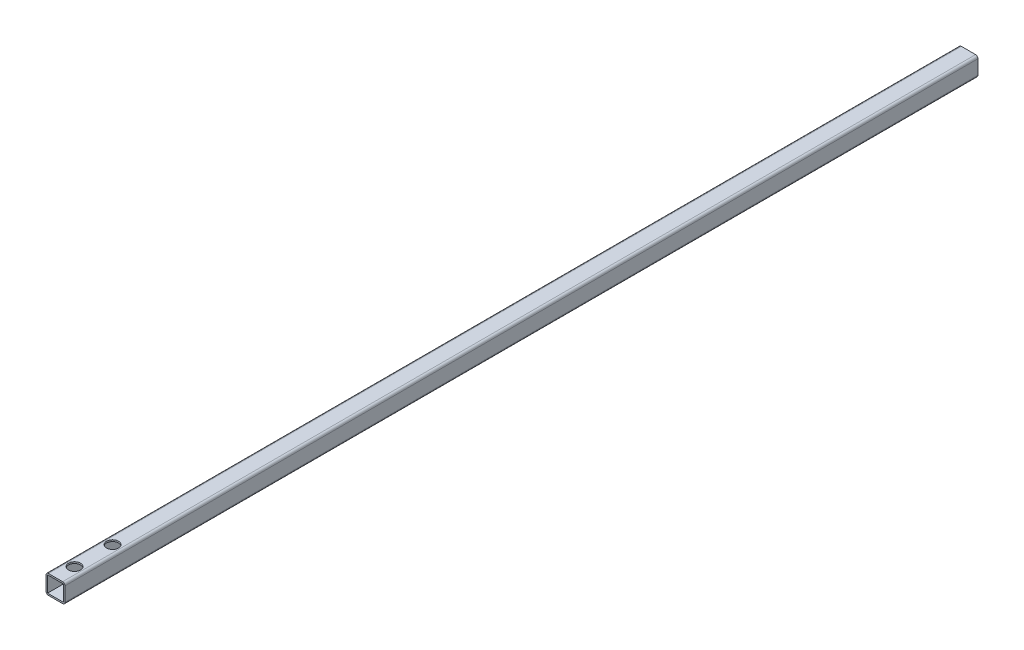
SolidWorks part; units mm, degrees
material "6063-T6"
ref_plane "Front Plane" through (0, 0, 0) normal (0, 0, 1) x (1, 0, 0)
ref_plane "Top Plane" through (0, 0, 0) normal (0, 1, 0) x (1, 0, 0)
ref_plane "Right Plane" through (0, 0, 0) normal (1, 0, 0) x (0, 0, -1)
sketch "Sketch1" plane through (0, 0, 0) normal (0, 0, 1) x (1, 0, 0)
  line L1 (-9.525, -12.7) -> (9.525, -12.7)
  line L2 (-12.7, -9.525) -> (-12.7, 9.525)
  line L3 (-9.525, 12.7) -> (9.525, 12.7)
  line L4 (12.7, -9.525) -> (12.7, 9.525)
  line L5 (-12.7, -12.7) -> (12.7, 12.7) construction
  line L6 (-12.7, 12.7) -> (12.7, -12.7) construction
  line L7 (-10.5918, -10.5918) -> (10.5918, -10.5918)
  line L8 (-10.5918, -10.5918) -> (-10.5918, 10.5918)
  line L9 (-10.5918, 10.5918) -> (10.5918, 10.5918)
  line L10 (10.5918, -10.5918) -> (10.5918, 10.5918)
  line L11 (-10.5918, -10.5918) -> (10.5918, 10.5918) construction
  line L12 (-10.5918, 10.5918) -> (10.5918, -10.5918) construction
  arc A0 (-9.525, -12.7) -> (-12.7, -9.525) centre (-9.525, -9.525) cw
  arc A1 (9.525, -12.7) -> (12.7, -9.525) centre (9.525, -9.525) ccw
  arc A2 (9.525, 12.7) -> (12.7, 9.525) centre (9.525, 9.525) cw
  arc A3 (-12.7, 9.525) -> (-9.525, 12.7) centre (-9.525, 9.525) cw
  point P0 (0, 0)
  point P6 (0, 0)
  dimension "D4" = 3.175
  dimension "D1" = 25.4
  dimension "D2" = 25.4
  dimension "D3" = 2.1082
extrude "Boss-Extrude1" add sketch "Sketch1" along normal blind 1219.2
sketch "Sketch2" plane through (0, 12.7, 0) normal (0, 1, 0) x (1, 0, 0)
  line L0 (9.525, -1219.2) -> (-9.525, -1219.2) construction
  line L2 (12.7, -1219.2) -> (12.7, 0) construction
  circle A0 centre (0, -1193.8) radius 8.001
  circle A1 centre (0, -1143) radius 8.001
  dimension "D3" = 16.002
  dimension "D1" = 25.4
  dimension "D2" = 12.7
  dimension "D4" = 2
extrude "Cut-Extrude1" cut sketch "Sketch2" against normal blind 1219.2
